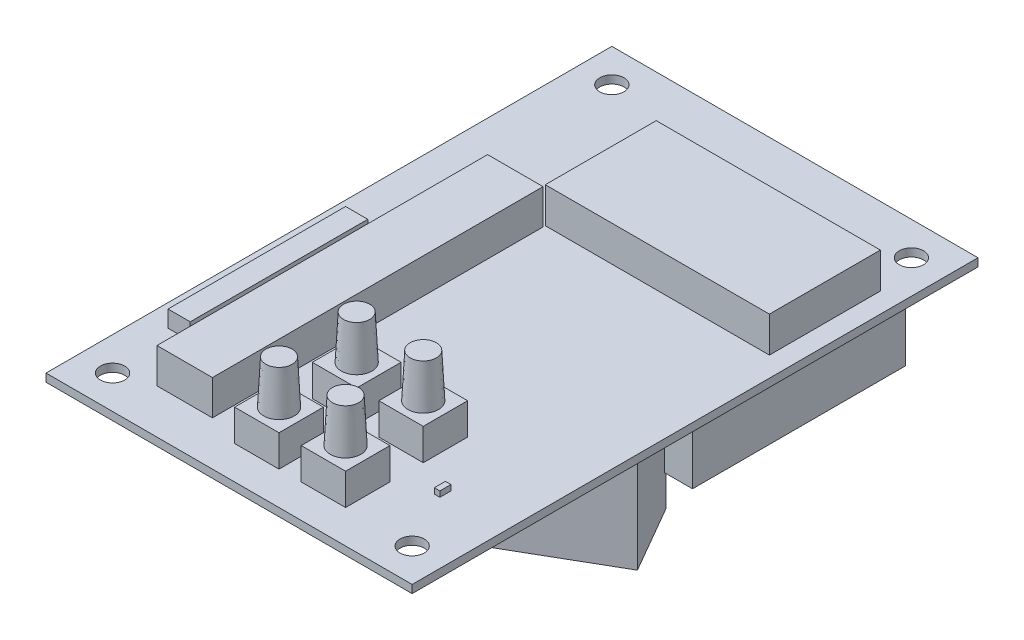
SolidWorks part; units mm, degrees
ref_plane "Front Plane" through (0, 0, 0) normal (0, 0, 1) x (1, 0, 0)
ref_plane "Top Plane" through (0, 0, 0) normal (0, 1, 0) x (1, 0, 0)
ref_plane "Right Plane" through (0, 0, 0) normal (1, 0, 0) x (0, 0, -1)
sketch "Sketch1" plane through (0, 0, 0) normal (0, 1, 0) x (1, 0, 0)
  line L1 (0, 0) -> (41.91, 0)
  line L2 (0, 0) -> (0, 64.77)
  line L3 (0, 64.77) -> (41.91, 64.77)
  line L4 (41.91, 0) -> (41.91, 64.77)
  dimension "D1" = 41.91
  dimension "D2" = 64.77
extrude "Board" add sketch "Sketch1" along normal blind 0.9144
sketch "ButtonBase" plane through (0, 0.9144, 0) normal (0, 1, 0) x (1, 0, 0)
  line L0 (0, 64.77) -> (0, 0) construction
  line L1 (17.78, 12.7) -> (22.86, 12.7)
  line L2 (17.78, 12.7) -> (17.78, 17.78)
  line L3 (17.78, 17.78) -> (22.86, 17.78)
  line L4 (22.86, 12.7) -> (22.86, 17.78)
  line L5 (17.78, 12.7) -> (22.86, 17.78) construction
  line L6 (17.78, 17.78) -> (22.86, 12.7) construction
  line L7 (0, 0) -> (41.91, 0) construction
  line L8 (30.48, 12.7) -> (30.48, 17.78)
  line L9 (25.4, 17.78) -> (30.48, 12.7) construction
  line L10 (25.4, 17.78) -> (30.48, 17.78)
  line L11 (25.4, 12.7) -> (25.4, 17.78)
  line L12 (25.4, 12.7) -> (30.48, 17.78) construction
  line L13 (25.4, 12.7) -> (30.48, 12.7)
  line L14 (30.48, 3.81) -> (30.48, 8.89)
  line L15 (25.4, 8.89) -> (30.48, 3.81) construction
  line L16 (25.4, 8.89) -> (30.48, 8.89)
  line L17 (25.4, 3.81) -> (25.4, 8.89)
  line L18 (25.4, 3.81) -> (30.48, 8.89) construction
  line L19 (25.4, 3.81) -> (30.48, 3.81)
  line L20 (22.86, 3.81) -> (22.86, 8.89)
  line L21 (17.78, 8.89) -> (22.86, 3.81) construction
  line L22 (17.78, 8.89) -> (22.86, 8.89)
  line L23 (17.78, 3.81) -> (17.78, 8.89)
  line L24 (17.78, 3.81) -> (22.86, 8.89) construction
  line L25 (17.78, 3.81) -> (22.86, 3.81)
  point P0 (20.32, 15.24)
  dimension "D1" = 20.32
  dimension "D2" = 15.24
  dimension "D3" = 5.08
  dimension "ButtonSepX" = 7.62
  dimension "ButtonSepY" = 8.89
  dimension "D4" = 2
  dimension "D5" = 2
extrude "Button" add sketch "ButtonBase" along normal blind 3.6068
sketch "Sketch4" plane through (0, 0.9144, 0) normal (0, 1, 0) x (1, 0, 0)
  line L0 (0, 0) -> (41.91, 0) construction
  line L1 (13.97, 43.18) -> (39.624, 43.18)
  line L2 (13.97, 43.18) -> (13.97, 55.88)
  line L3 (13.97, 55.88) -> (39.624, 55.88)
  line L4 (39.624, 43.18) -> (39.624, 55.88)
  line L5 (0, 64.77) -> (0, 0) construction
  dimension "D1" = 43.18
  dimension "D2" = 13.97
  dimension "D3" = 12.7
  dimension "D4" = 25.654
extrude "LiPo" add sketch "Sketch4" along normal blind 4.064
hole_wizard "7/64 (0.10938) Diameter Hole1" positions "Sketch7" profile "Sketch6" hole size "7/64" standard "ANSI Inch"
sketch "Sketch7" plane through (0, 0.9144, 0) normal (0, 1, 0) x (1, 0, 0)
  line L0 (0, 0) -> (41.91, 0) construction
  line L1 (0, 64.77) -> (0, 0) construction
  point P0 (3.81, 60.96)
  point P2 (38.1, 60.96)
  point P4 (38.1, 3.81)
  point P6 (3.81, 3.81)
  dimension "D1" = 3.81
  dimension "D2" = 3.81
  dimension "D3" = 38.1
  dimension "D4" = 3.81
  dimension "D5" = 60.96
sketch "Sketch6" plane through (3.81, 0.9144, -60.96) normal (1, 0, 0) x (0, 0, 1)
  line L0 (0, 0) -> (0, 26.2347)
  line L1 (0, 26.2347) -> (1.3891, 25.4)
  line L2 (1.3891, 25.4) -> (1.3891, 0)
  line L5 (1.3891, 0) -> (0, 0)
  line L10 (0, 26.2347) -> (-1.3891, 25.4) construction
  line L11 (0, -6.35) -> (0, 107.95) construction
  dimension "Hole Dia." = 2.7783
  dimension "Hole Depth" = 25.4
  dimension "Drill Angle" = 118
sketch "Sketch8" plane through (0, 0.9144, 0) normal (0, 1, 0) x (1, 0, 0)
  line L0 (0, 0) -> (41.91, 0) construction
  line L1 (34.2265, 10.2235) -> (34.8615, 10.2235)
  line L2 (34.2265, 10.2235) -> (34.2265, 11.4935)
  line L3 (34.2265, 11.4935) -> (34.8615, 11.4935)
  line L4 (34.8615, 10.2235) -> (34.8615, 11.4935)
  line L5 (34.2265, 10.2235) -> (34.8615, 11.4935) construction
  line L6 (34.2265, 11.4935) -> (34.8615, 10.2235) construction
  line L8 (0, 64.77) -> (0, 0) construction
  point P0 (34.544, 10.8585)
  dimension "D1" = 10.8585
  dimension "D2" = 34.544
  dimension "D3" = 0.635
  dimension "D4" = 1.27
extrude "LED" add sketch "Sketch8" along normal blind 0.635
sketch "Sketch10" plane through (0, 0, 0) normal (0, -1, 0) x (1, 0, 0)
  line L0 (41.4782, -26.2182) -> (28.9179, -18.9665)
  line L1 (41.4782, -26.2182) -> (36.9824, -34.0052)
  line L2 (28.9179, -18.9665) -> (24.4221, -26.7535)
  line L3 (36.9824, -34.0052) -> (24.4221, -26.7535)
  line L4 (41.4782, -26.2182) -> (24.4221, -26.7535) construction
  line L5 (28.9179, -18.9665) -> (36.9824, -34.0052) construction
  line L6 (41.91, 0) -> (41.91, -64.77) construction
  line L7 (0, -64.77) -> (0, 0) construction
  line L9 (0, 0) -> (41.91, 0) construction
  point P0 (26.67, -22.86)
  point P1 (32.9502, -26.4859)
  dimension "D1" = 26.67
  dimension "D2" = 22.86
  dimension "D3" = 8.9916
  dimension "D4" = 14.5034
  dimension "D5" = 60
extrude "PowerJack" add sketch "Sketch10" along normal blind 10.9982
sketch "Sketch11" plane through (0, 0, 0) normal (0, -1, 0) x (1, 0, 0)
  line L0 (19.3929, -57.912) -> (12.8651, -50.3174)
  line L1 (40.4749, -57.912) -> (40.4749, -33.528)
  line L2 (40.4749, -57.912) -> (19.3929, -57.912)
  line L3 (19.3929, -57.912) -> (19.3929, -33.528) construction
  line L4 (40.4749, -33.528) -> (19.3929, -33.528)
  line L5 (12.8651, -50.3174) -> (12.8651, -41.1226)
  line L6 (12.8651, -41.1226) -> (19.3929, -33.528)
  line L7 (12.8651, -45.72) -> (40.4749, -45.72) construction
  line L10 (0, -64.77) -> (0, 0) construction
  line L11 (0, 0) -> (41.91, 0) construction
  line L12 (26.67, -45.72) -> (26.67, -33.528) construction
  line L13 (26.67, -33.528) -> (26.67, -57.912) construction
  point P8 (26.67, -45.72)
  dimension "D1" = 24.384
  dimension "D2" = 6.5278
  dimension "D3" = 27.6098
  dimension "D4" = 7.5946
  dimension "D5" = 26.67
  dimension "D6" = 45.72
extrude "XBee" add sketch "Sketch11" along normal blind 7.09
sketch "Sketch12" plane through (0, 4.5212, 0) normal (0, 1, 0) x (1, 0, 0)
  line L0 (20.32, 17.78) -> (20.32, 12.7) construction
  line L1 (22.86, 17.78) -> (17.78, 17.78) construction
  line L2 (17.78, 12.7) -> (22.86, 12.7) construction
  line L3 (20.32, 12.7) -> (20.32, 3.81) construction
  line L4 (17.78, 3.81) -> (22.86, 3.81) construction
  line L5 (17.78, 15.24) -> (30.48, 15.24) construction
  line L6 (17.78, 17.78) -> (17.78, 12.7) construction
  line L7 (30.48, 12.7) -> (30.48, 17.78) construction
  circle A0 centre (20.32, 15.24) radius 1.7526
  circle A1 centre (27.94, 15.24) radius 1.7526
  circle A2 centre (27.94, 6.35) radius 1.7526
  circle A3 centre (20.32, 6.35) radius 1.7526
  point P15 (20.32, 15.24)
  point P17 (27.94, 15.24)
  point P19 (27.94, 6.35)
  point P20 (20.32, 6.35)
  dimension "D5" = 3.5052
  dimension "D3" = 7.62
  dimension "D4" = 8.89
  dimension "D1" = 2
  dimension "D2" = 2
  dimension "D6" = 2
  dimension "D7" = 2
extrude "ButtonPlunger" add sketch "Sketch12" along normal blind 5
draft "Plunger Taper" type of draft neutral plane draft angle 2.87 faces to draft 4 face at (27.94, 9.5212, -4.5974) face at (27.94, 9.5212, -13.4874) face at (20.32, 9.5212, -13.4874) face at (20.32, 9.5212, -4.5974) neutral plane through (0, 4.5212, 0) neutral plane normal (0, 1, 0) parameters "D1"=2.87
sketch "Sketch13" plane through (0, 0.9144, 0) normal (0, 1, 0) x (1, 0, 0)
  line L0 (0, 64.77) -> (0, 0) construction
  line L1 (7.62, 5.08) -> (13.97, 5.08)
  line L2 (7.62, 5.08) -> (7.62, 42.926)
  line L3 (7.62, 42.926) -> (13.97, 42.926)
  line L4 (13.97, 5.08) -> (13.97, 42.926)
  line L5 (0, 0) -> (41.91, 0) construction
  dimension "D1" = 7.62
  dimension "D2" = 5.08
  dimension "D3" = 6.35
  dimension "D4" = 37.846
extrude "ATMEL" add sketch "Sketch13" along normal blind 4
sketch "Sketch15" plane through (0, 0, 0) normal (0, -1, 0) x (-1, 0, 0)
  line L0 (0, 64.77) -> (0, 0) construction
  line L1 (-2.54, 11.43) -> (-5.08, 11.43)
  line L2 (-2.54, 11.43) -> (-2.54, 31.75)
  line L3 (-2.54, 31.75) -> (-5.08, 31.75)
  line L4 (-5.08, 11.43) -> (-5.08, 31.75)
  line L5 (0, 0) -> (-41.91, 0) construction
  dimension "D1" = 2.54
  dimension "D2" = 20.32
  dimension "D3" = 2.54
  dimension "D4" = 11.43
extrude "Headers" add sketch "Sketch15" along normal blind 8.89 and the other way blind 2.8194
